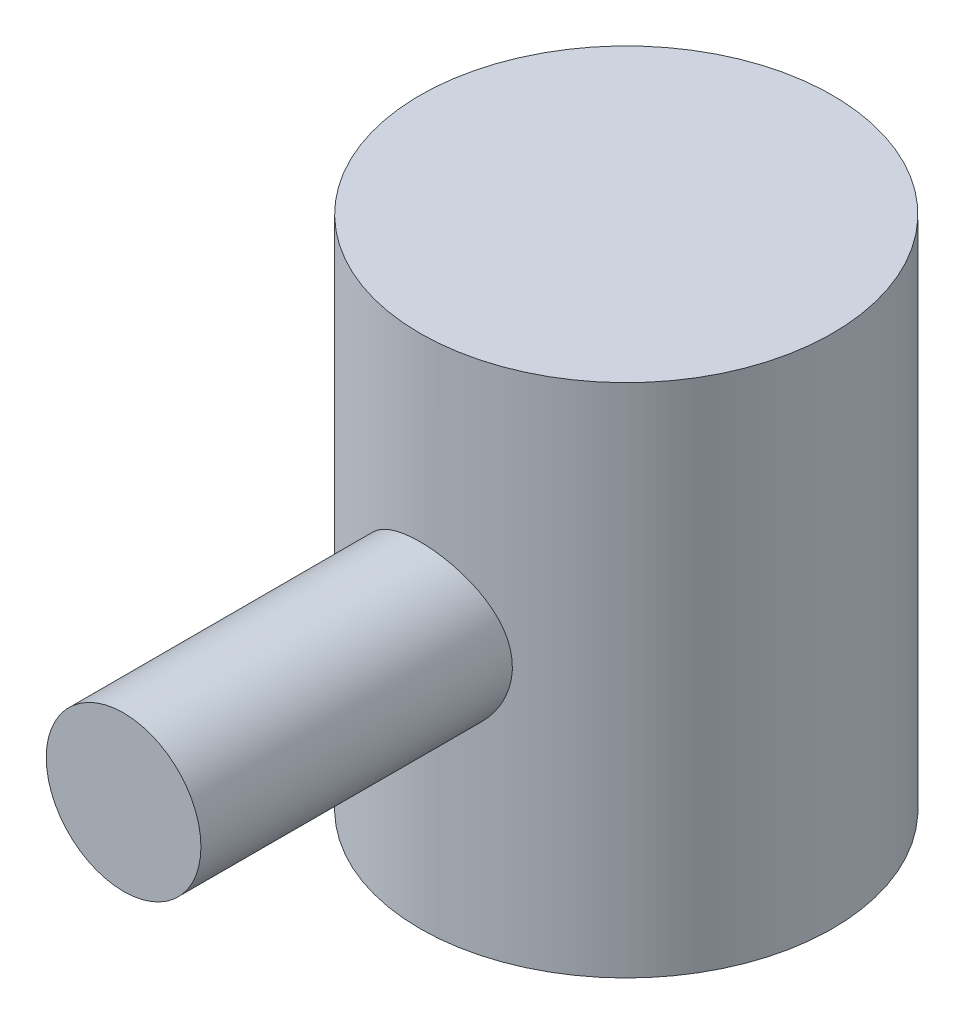
SolidWorks part; units mm, degrees
ref_plane "前视基准面" through (0, 0, 0) normal (0, 0, 1) x (1, 0, 0)
ref_plane "上视基准面" through (0, 0, 0) normal (0, 1, 0) x (1, 0, 0)
ref_plane "右视基准面" through (0, 0, 0) normal (1, 0, 0) x (0, 0, -1)
other "Configuration Table"
sketch "草图1" plane through (0, 0, 0) normal (0, 1, 0) x (1, 0, 0)
  circle A0 centre (0, 0) radius 80
  dimension "D1" = 160
extrude "凸台-拉伸1" add sketch "草图1" along normal blind 200
sketch "草图2" plane through (0, 0, 0) normal (0, 0, 1) x (1, 0, 0)
  line L0 (0, 0) -> (0, 100) construction
  circle A0 centre (0, 100) radius 30
  dimension "D1" = 60
  dimension "D2" = 100
extrude "凸台-拉伸2" add sketch "草图2" along normal blind 195
sketch "草图3" plane through (0, 0, 0) normal (0, -1, 0) x (1, 0, 0)
  circle A0 centre (0, 0) radius 37.5 construction
  circle A1 centre (0, 37.5) radius 2
extrude "切除-拉伸1" cut sketch "草图3" against normal blind 2
pattern_circular "阵列(圆周)1" count 4 over 360 about axis through (0, 0, -0.0235) along (0, 1, 0) of "切除-拉伸1"
